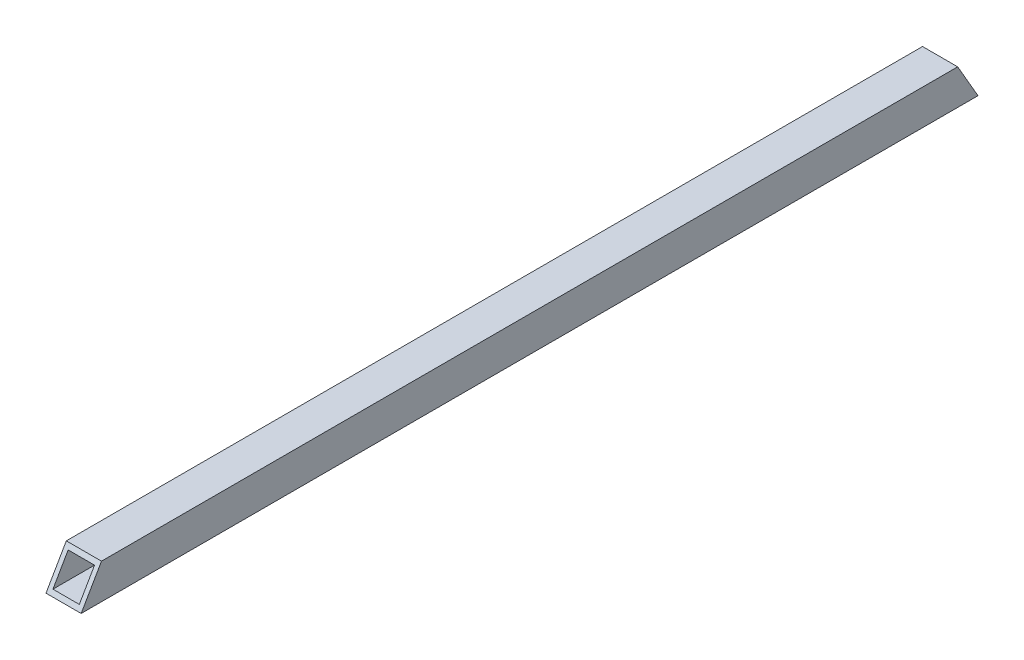
SolidWorks part; units mm, degrees
ref_plane "Front Plane" through (0, 0, 0) normal (0, 0, 1) x (1, 0, 0)
ref_plane "Top Plane" through (0, 0, 0) normal (0, 1, 0) x (1, 0, 0)
ref_plane "Right Plane" through (0, 0, 0) normal (1, 0, 0) x (0, 0, -1)
sketch "Sketch1" plane through (0, 0, 0) normal (0, 0, 1) x (1, 0, 0)
  line L1 (12.7, -12.7) -> (-12.7, -12.7)
  line L2 (12.7, -12.7) -> (12.7, 12.7)
  line L3 (12.7, 12.7) -> (-12.7, 12.7)
  line L4 (-12.7, -12.7) -> (-12.7, 12.7)
  line L5 (12.7, -12.7) -> (-12.7, 12.7) construction
  line L6 (12.7, 12.7) -> (-12.7, -12.7) construction
  line L7 (9.525, -9.525) -> (-9.525, -9.525)
  line L8 (9.525, -9.525) -> (9.525, 9.525)
  line L9 (9.525, 9.525) -> (-9.525, 9.525)
  line L10 (-9.525, -9.525) -> (-9.525, 9.525)
  line L11 (9.525, -9.525) -> (-9.525, 9.525) construction
  line L12 (9.525, 9.525) -> (-9.525, -9.525) construction
  point P0 (0, 0)
  point P6 (0, 0)
  dimension "D1" = 25.4
  dimension "D2" = 25.4
  dimension "D3" = 3.175
extrude "Boss-Extrude1" add sketch "Sketch1" along normal blind 323.85
ref_plane "Plane1" through (0, 137.0562, 237.3882) normal (0, 0.5, 0.866) x (1, 0, 0)
sketch "Sketch2" plane through (0, 137.0562, 237.3882) normal (0, 0.5, 0.866) x (1, 0, 0)
  line L0 (-12.7, -172.9235) -> (12.7, -172.9235)
  line L1 (-12.7, -172.9235) -> (12.7, -172.9235)
  line L2 (-12.7, -172.9235) -> (-12.7, -143.5941)
  line L3 (-12.7, -172.9235) -> (-12.7, -143.5941)
  line L4 (-12.7, -143.5941) -> (12.7, -143.5941)
  line L5 (-12.7, -143.5941) -> (12.7, -143.5941)
  line L6 (12.7, -143.5941) -> (12.7, -172.9235)
  line L7 (12.7, -143.5941) -> (12.7, -172.9235)
extrude "Cut-Extrude1" cut sketch "Sketch2" along normal through all
mirror "Mirror2" about plane through (0, 0, 0) normal (0, 0, 1) of "Cut-Extrude1", "Boss-Extrude1"
